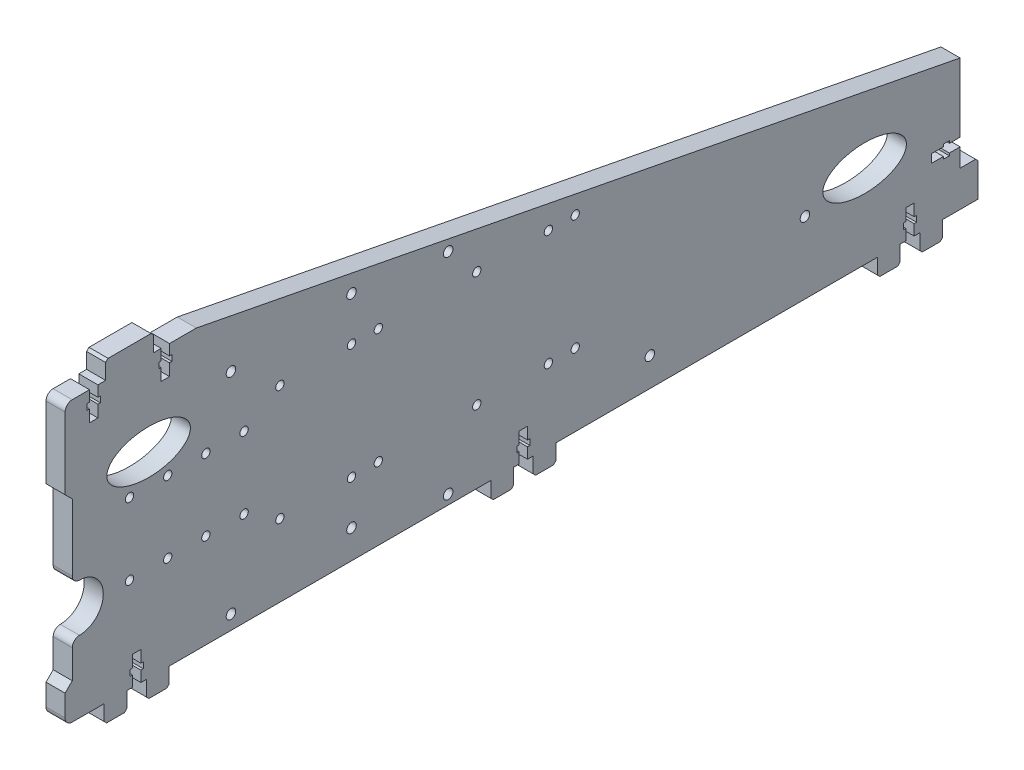
SolidWorks part; units mm, degrees
ref_plane "Front Plane" through (0, 0, 0) normal (0, 0, 1) x (1, 0, 0)
ref_plane "Top Plane" through (0, 0, 0) normal (0, 1, 0) x (1, 0, 0)
ref_plane "Right Plane" through (0, 0, 0) normal (1, 0, 0) x (0, 0, -1)
sketch "Sketch1" plane through (0, 0, 0) normal (1, 0, 0) x (0, 0, -1)
  line L0 (377.0111, 9.4389) -> (384.5111, 9.4389)
  line L1 (384.5111, 9.4389) -> (384.5111, 24.4389)
  line L2 (384.5111, 24.4389) -> (377.0111, 24.4389)
  line L3 (377.0111, 24.4389) -> (377.0111, 32.1889)
  line L4 (377.0111, 32.1889) -> (372.5111, 32.1889)
  line L5 (372.5111, 32.1889) -> (372.5111, 31.1889)
  line L6 (372.5111, 31.1889) -> (370.0111, 31.1889)
  line L7 (370.0111, 31.1889) -> (370.0111, 32.1889)
  line L8 (370.0111, 32.1889) -> (365.0111, 32.1889)
  line L9 (365.0111, 32.1889) -> (365.0111, 35.6889)
  line L10 (365.0111, 35.6889) -> (370.0111, 35.6889)
  line L11 (370.0111, 35.6889) -> (370.0111, 36.6889)
  line L12 (370.0111, 36.6889) -> (372.5111, 36.6889)
  line L13 (372.5111, 36.6889) -> (372.5111, 35.6889)
  line L14 (372.5111, 35.6889) -> (377.0111, 35.6889)
  line L15 (377.0111, 35.6889) -> (377.0111, 64.4389)
  line L16 (377.0111, 64.4389) -> (57.0111, 126.4389)
  line L17 (57.0111, 126.4389) -> (45.7611, 126.4389)
  line L18 (45.7611, 126.4389) -> (45.7611, 121.9389)
  line L19 (45.7611, 121.9389) -> (46.7611, 121.9389)
  line L20 (46.7611, 121.9389) -> (46.7611, 119.4389)
  line L21 (46.7611, 119.4389) -> (45.7611, 119.4389)
  line L22 (45.7611, 119.4389) -> (45.7611, 114.4389)
  line L23 (45.7611, 114.4389) -> (42.2611, 114.4389)
  line L24 (42.2611, 114.4389) -> (42.2611, 119.4389)
  line L25 (42.2611, 119.4389) -> (41.2611, 119.4389)
  line L26 (41.2611, 119.4389) -> (41.2611, 121.9389)
  line L27 (41.2611, 121.9389) -> (42.2611, 121.9389)
  line L28 (42.2611, 121.9389) -> (42.2611, 126.4389)
  line L29 (42.2611, 126.4389) -> (39.0111, 126.4389)
  line L30 (39.0111, 126.4389) -> (39.0111, 132.9389)
  line L31 (39.0111, 132.9389) -> (38.0111, 133.9389)
  line L32 (38.0111, 133.9389) -> (20.0111, 133.9389)
  line L33 (20.0111, 133.9389) -> (19.0111, 132.9389)
  line L34 (19.0111, 132.9389) -> (19.0111, 126.4389)
  line L35 (19.0111, 126.4389) -> (15.7611, 126.4389)
  line L36 (15.7611, 126.4389) -> (15.7611, 121.9389)
  line L37 (15.7611, 121.9389) -> (16.7611, 121.9389)
  line L38 (16.7611, 121.9389) -> (16.7611, 119.4389)
  line L39 (16.7611, 119.4389) -> (15.7611, 119.4389)
  line L40 (15.7611, 119.4389) -> (15.7611, 114.4389)
  line L41 (15.7611, 114.4389) -> (12.2611, 114.4389)
  line L42 (12.2611, 114.4389) -> (12.2611, 119.4389)
  line L43 (12.2611, 119.4389) -> (11.2611, 119.4389)
  line L44 (11.2611, 119.4389) -> (11.2611, 121.9389)
  line L45 (11.2611, 121.9389) -> (12.2611, 121.9389)
  line L46 (12.2611, 121.9389) -> (12.2611, 126.4389)
  line L47 (12.2611, 126.4389) -> (5.0111, 126.4389)
  line L48 (2.0111, 123.4389) -> (2.0111, 93.4389)
  line L49 (2.0111, 93.4389) -> (5.0111, 90.4389)
  line L50 (5.0111, 90.4389) -> (5.0111, 62.4389)
  line L51 (5.0111, 36.4389) -> (5.0111, 24.4389)
  line L52 (5.0111, 24.4389) -> (2.0111, 21.4389)
  line L53 (2.0111, 21.4389) -> (2.0111, 12.4389)
  line L54 (5.0111, 9.4389) -> (18.3861, 9.4389)
  line L55 (18.3861, 9.4389) -> (18.3861, 2.9389)
  line L56 (18.3861, 2.9389) -> (19.3861, 1.9389)
  line L57 (19.3861, 1.9389) -> (26.8861, 1.9389)
  line L58 (26.8861, 1.9389) -> (27.8861, 2.9389)
  line L59 (27.8861, 2.9389) -> (27.8861, 9.4389)
  line L60 (27.8861, 9.4389) -> (30.2611, 9.4389)
  line L61 (30.2611, 9.4389) -> (30.2611, 13.9389)
  line L62 (30.2611, 13.9389) -> (29.2611, 13.9389)
  line L63 (29.2611, 13.9389) -> (29.2611, 16.4389)
  line L64 (29.2611, 16.4389) -> (30.2611, 16.4389)
  line L65 (30.2611, 16.4389) -> (30.2611, 21.4389)
  line L66 (30.2611, 21.4389) -> (33.7611, 21.4389)
  line L67 (33.7611, 21.4389) -> (33.7611, 16.4389)
  line L68 (33.7611, 16.4389) -> (34.7611, 16.4389)
  line L69 (34.7611, 16.4389) -> (34.7611, 13.9389)
  line L70 (34.7611, 13.9389) -> (33.7611, 13.9389)
  line L71 (33.7611, 13.9389) -> (33.7611, 9.4389)
  line L72 (33.7611, 9.4389) -> (36.1361, 9.4389)
  line L73 (36.1361, 9.4389) -> (36.1361, 2.9389)
  line L74 (36.1361, 2.9389) -> (37.1361, 1.9389)
  line L75 (37.1361, 1.9389) -> (44.6361, 1.9389)
  line L76 (44.6361, 1.9389) -> (45.6361, 2.9389)
  line L77 (45.6361, 2.9389) -> (45.6361, 9.4389)
  line L78 (45.6361, 9.4389) -> (180.3861, 9.4389)
  line L79 (180.3861, 9.4389) -> (180.3861, 2.9389)
  line L80 (180.3861, 2.9389) -> (181.3861, 1.9389)
  line L81 (181.3861, 1.9389) -> (188.8861, 1.9389)
  line L82 (188.8861, 1.9389) -> (189.8861, 2.9389)
  line L83 (189.8861, 2.9389) -> (189.8861, 9.4389)
  line L84 (189.8861, 9.4389) -> (192.2611, 9.4389)
  line L85 (192.2611, 9.4389) -> (192.2611, 13.9389)
  line L86 (192.2611, 13.9389) -> (191.2611, 13.9389)
  line L87 (191.2611, 13.9389) -> (191.2611, 16.4389)
  line L88 (191.2611, 16.4389) -> (192.2611, 16.4389)
  line L89 (192.2611, 16.4389) -> (192.2611, 21.4389)
  line L90 (192.2611, 21.4389) -> (195.7611, 21.4389)
  line L91 (195.7611, 21.4389) -> (195.7611, 16.4389)
  line L92 (195.7611, 16.4389) -> (196.7611, 16.4389)
  line L93 (196.7611, 16.4389) -> (196.7611, 13.9389)
  line L94 (196.7611, 13.9389) -> (195.7611, 13.9389)
  line L95 (195.7611, 13.9389) -> (195.7611, 9.4389)
  line L96 (195.7611, 9.4389) -> (198.1361, 9.4389)
  line L97 (198.1361, 9.4389) -> (198.1361, 2.9389)
  line L98 (198.1361, 2.9389) -> (199.1361, 1.9389)
  line L99 (199.1361, 1.9389) -> (206.6361, 1.9389)
  line L100 (206.6361, 1.9389) -> (207.6361, 2.9389)
  line L101 (207.6361, 2.9389) -> (207.6361, 9.4389)
  line L102 (207.6361, 9.4389) -> (342.3861, 9.4389)
  line L103 (342.3861, 9.4389) -> (342.3861, 2.9389)
  line L104 (342.3861, 2.9389) -> (343.3861, 1.9389)
  line L105 (343.3861, 1.9389) -> (350.8861, 1.9389)
  line L106 (350.8861, 1.9389) -> (351.8861, 2.9389)
  line L107 (351.8861, 2.9389) -> (351.8861, 9.4389)
  line L108 (351.8861, 9.4389) -> (354.2611, 9.4389)
  line L109 (354.2611, 9.4389) -> (354.2611, 13.9389)
  line L110 (354.2611, 13.9389) -> (353.2611, 13.9389)
  line L111 (353.2611, 13.9389) -> (353.2611, 16.4389)
  line L112 (353.2611, 16.4389) -> (354.2611, 16.4389)
  line L113 (354.2611, 16.4389) -> (354.2611, 21.4389)
  line L114 (354.2611, 21.4389) -> (357.7611, 21.4389)
  line L115 (357.7611, 21.4389) -> (357.7611, 16.4389)
  line L116 (357.7611, 16.4389) -> (358.7611, 16.4389)
  line L117 (358.7611, 16.4389) -> (358.7611, 13.9389)
  line L118 (358.7611, 13.9389) -> (357.7611, 13.9389)
  line L119 (357.7611, 13.9389) -> (357.7611, 9.4389)
  line L120 (357.7611, 9.4389) -> (360.1361, 9.4389)
  line L121 (360.1361, 9.4389) -> (360.1361, 2.9389)
  line L122 (360.1361, 2.9389) -> (361.1361, 1.9389)
  line L123 (361.1361, 1.9389) -> (368.6361, 1.9389)
  line L124 (368.6361, 1.9389) -> (369.6361, 2.9389)
  line L125 (369.6361, 2.9389) -> (369.6361, 9.4389)
  line L126 (369.6361, 9.4389) -> (377.0111, 9.4389)
  arc A0 (5.0111, 126.4389) -> (2.0111, 123.4389) centre (5.0111, 123.4389) ccw
  arc A1 (5.0111, 62.4389) -> (8.0111, 59.4389) centre (8.0111, 62.4389) ccw
  arc A2 (8.0111, 39.4389) -> (8.0111, 59.4389) centre (8.0111, 49.4389) ccw
  arc A3 (8.0111, 39.4389) -> (5.0111, 36.4389) centre (8.0111, 36.4389) ccw
  arc A4 (2.0111, 12.4389) -> (5.0111, 9.4389) centre (5.0111, 12.4389) ccw
  circle A5 centre (71.5111, 15.4389) radius 2
  circle A6 centre (162.5111, 13.4389) radius 2
  circle A7 centre (71.5111, 103.4389) radius 2
  circle A8 centre (162.5111, 101.4389) radius 2
  circle A9 centre (122.0111, 21.4389) radius 2
  circle A10 centre (122.0111, 106.4389) radius 2
  circle A11 centre (247.0111, 21.4389) radius 2
  circle A12 centre (312.0111, 39.4389) radius 2
  ellipse E0 centre (337.0111, 44.4389) end of major axis (354.5111, 44.4389) minor radius 9.25
  ellipse E1 centre (37.0111, 91.4389) end of major axis (54.5111, 91.4389) minor radius 9.25
extrude "Extrude1" add sketch "Sketch1" along normal blind 8
sketch "Sketch2" plane through (0, 114.4389, 0) normal (0, 1, 0) x (1, 0, 0)
  line L0 (0, 45.7611) -> (8, 42.2611)
  circle A0 centre (4, 44.0111) radius 1
  dimension "D1" = 2
extrude "Extrude2" cut sketch "Sketch2" against normal blind 1 contours A0
sketch "Sketch3" plane through (0, 114.4389, 0) normal (0, 1, 0) x (1, 0, 0)
  line L0 (8, 15.7611) -> (0, 12.2611)
  circle A0 centre (4, 14.0111) radius 1
  dimension "D1" = 2
extrude "Extrude3" cut sketch "Sketch3" against normal blind 1 contours A0
sketch "Sketch4" plane through (0, 21.4389, 0) normal (0, -1, 0) x (1, 0, 0)
  line L0 (0, -30.2611) -> (8, -33.7611)
  circle A0 centre (4, -32.0111) radius 1
  dimension "D1" = 2
extrude "Extrude4" cut sketch "Sketch4" against normal blind 1 contours A0
sketch "Sketch5" plane through (0, 21.4389, 0) normal (0, -1, 0) x (1, 0, 0)
  line L0 (0, -357.7611) -> (8, -354.2611)
  circle A0 centre (4, -356.0111) radius 1
  dimension "D1" = 2
extrude "Extrude5" cut sketch "Sketch5" against normal blind 1 contours A0
sketch "Sketch6" plane through (0, 0, -365.0111) normal (0, 0, -1) x (-1, 0, 0)
  line L0 (-8, 35.6889) -> (0, 32.1889) construction
  circle A0 centre (-4, 33.9389) radius 1
  dimension "D1" = 2
extrude "Extrude6" cut sketch "Sketch6" against normal blind 1
chamfer "Chamfer1" distance 1 angle 45 1 edges at (4, 24.4389, -384.5111)
sketch "Sketch7" plane through (0, 0, 0) normal (-1, 0, 0) x (0, 0, 1)
  line L1 (-122.0111, 21.4389) -> (-122.0111, 106.4389) construction
  line L2 (-122.0111, 63.9389) -> (-92.0111, 63.9389) construction
  line L3 (-92.0111, 63.9389) -> (-92.0111, 39.7889) construction
  line L4 (-92.0111, 63.9389) -> (-92.0111, 88.0889) construction
  line L5 (-92.0111, 39.7889) -> (-174.5111, 39.7889) construction
  line L6 (-92.0111, 63.9389) -> (-77.0111, 63.9389) construction
  line L7 (-77.0111, 63.9389) -> (-77.0111, 48.9389) construction
  line L8 (-77.0111, 48.9389) -> (-61.0111, 48.9389) construction
  line L9 (-61.0111, 48.9389) -> (-61.0111, 78.9389) construction
  line L10 (-61.0111, 78.9389) -> (-77.0111, 78.9389) construction
  circle A2 centre (-92.0111, 88.0889) radius 1.75
  circle A3 centre (-92.0111, 39.7889) radius 1.75
  circle A4 centre (-174.5111, 39.7889) radius 1.75
  circle A5 centre (-174.5111, 88.0889) radius 1.75
  circle A6 centre (-77.0111, 48.9389) radius 1.75
  circle A7 centre (-61.0111, 48.9389) radius 1.75
  circle A8 centre (-61.0111, 78.9389) radius 1.75
  circle A9 centre (-77.0111, 78.9389) radius 1.75
  circle A10 centre (-45.0111, 48.9389) radius 1.75
  circle A11 centre (-45.0111, 78.9389) radius 1.75
  circle A12 centre (-29.0111, 48.9389) radius 1.75
  circle A13 centre (-29.0111, 78.9389) radius 1.75
  circle A14 centre (-122.0111, 88.0889) radius 1.75
  circle A15 centre (-122.0111, 39.7889) radius 1.75
  circle A16 centre (-204.5111, 88.0889) radius 1.75
  circle A17 centre (-204.5111, 39.7889) radius 1.75
  circle A18 centre (-133.2611, 88.0889) radius 1.75
  circle A19 centre (-133.2611, 39.7889) radius 1.75
  circle A20 centre (-215.7611, 88.0889) radius 1.75
  circle A21 centre (-215.7611, 39.7889) radius 1.75
  dimension "D1" = 30
  dimension "D4" = 3.5
  dimension "D5" = 3.5
  dimension "D7" = 48.3
  dimension "D8" = 52.5
  dimension "D9" = 48.3
  dimension "D10" = 3.5
  dimension "D16" = 3.5
  dimension "D17" = 3.5
  dimension "D18" = 3.5
  dimension "D19" = 3.5
  dimension "D20" = 16
  dimension "D21" = 30
  dimension "D22" = 3.5
  dimension "D23" = 16
  dimension "D24" = 3.5
  dimension "D2" = 24.15
  dimension "D3" = 24.15
  dimension "D6" = 82.5
  dimension "D11" = 15
  dimension "D12" = 15
  dimension "D13" = 30
  dimension "D14" = 16
  dimension "D15" = 16
extrude "Cut-Extrude1" cut sketch "Sketch7" against normal through all
